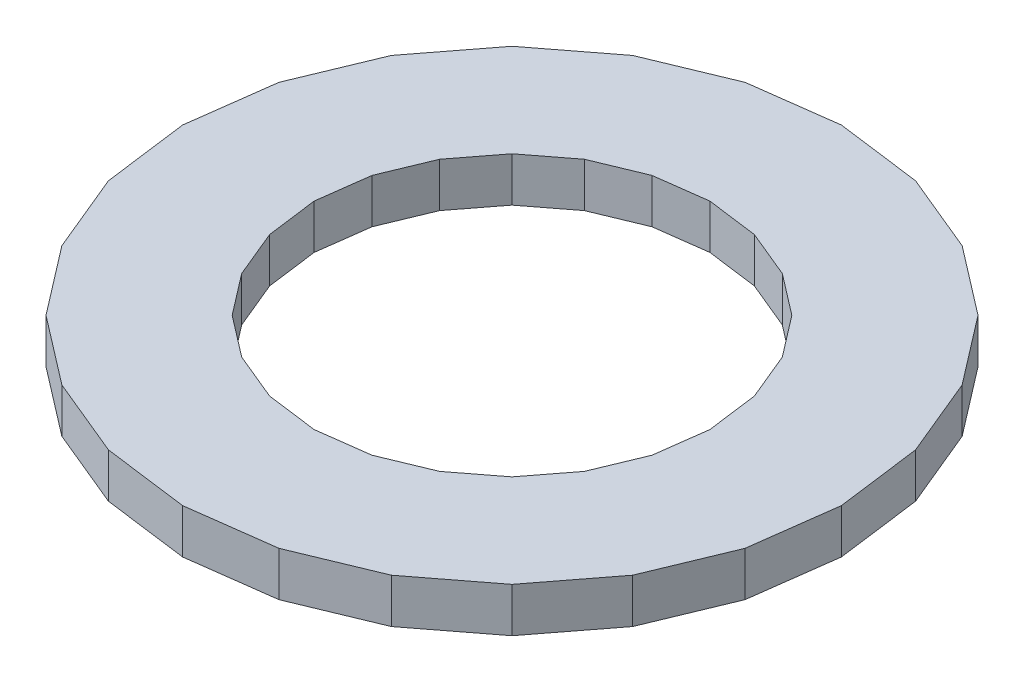
SolidWorks part; units mm, degrees
ref_plane "Front Plane" through (0, 0, 0) normal (0, 0, 1) x (1, 0, 0)
ref_plane "Top Plane" through (0, 0, 0) normal (0, 1, 0) x (1, 0, 0)
ref_plane "Right Plane" through (0, 0, 0) normal (1, 0, 0) x (0, 0, -1)
sketch "Sketch2" plane through (0, 0, 0) normal (0, 1, 0) x (1, 0, 0)
  line L0 (0, 0) -> (-84.7206, 0) construction
  line L1 (-141.0828, 0) -> (-136.2755, -36.5149)
  line L2 (-136.2755, -36.5149) -> (-122.1813, -70.5414)
  line L3 (-122.1813, -70.5414) -> (-99.7606, -99.7606)
  line L4 (-99.7606, -99.7606) -> (-70.5414, -122.1813)
  line L5 (-70.5414, -122.1813) -> (-36.5149, -136.2755)
  line L6 (-36.5149, -136.2755) -> (0, -141.0828)
  line L7 (0, -141.0828) -> (36.5149, -136.2755)
  line L8 (36.5149, -136.2755) -> (70.5414, -122.1813)
  line L9 (70.5414, -122.1813) -> (99.7606, -99.7606)
  line L10 (99.7606, -99.7606) -> (122.1813, -70.5414)
  line L11 (122.1813, -70.5414) -> (136.2755, -36.5149)
  line L12 (136.2755, -36.5149) -> (141.0828, 0)
  line L13 (141.0828, 0) -> (136.2755, 36.5149)
  line L14 (136.2755, 36.5149) -> (122.1813, 70.5414)
  line L15 (122.1813, 70.5414) -> (99.7606, 99.7606)
  line L16 (99.7606, 99.7606) -> (70.5414, 122.1813)
  line L17 (70.5414, 122.1813) -> (36.5149, 136.2755)
  line L18 (36.5149, 136.2755) -> (0, 141.0828)
  line L19 (0, 141.0828) -> (-36.5149, 136.2755)
  line L20 (-36.5149, 136.2755) -> (-70.5414, 122.1813)
  line L21 (-70.5414, 122.1813) -> (-99.7606, 99.7606)
  line L22 (-99.7606, 99.7606) -> (-122.1813, 70.5414)
  line L23 (-122.1813, 70.5414) -> (-136.2755, 36.5149)
  line L24 (-136.2755, 36.5149) -> (-141.0828, 0)
  line L25 (-84.7206, 0) -> (-81.8338, -21.9273)
  line L26 (-81.8338, -21.9273) -> (-73.3702, -42.3603)
  line L27 (-73.3702, -42.3603) -> (-59.9065, -59.9065)
  line L28 (-59.9065, -59.9065) -> (-42.3603, -73.3702)
  line L29 (-42.3603, -73.3702) -> (-21.9273, -81.8338)
  line L30 (-21.9273, -81.8338) -> (0, -84.7206)
  line L31 (0, -84.7206) -> (21.9273, -81.8338)
  line L32 (21.9273, -81.8338) -> (42.3603, -73.3702)
  line L33 (42.3603, -73.3702) -> (59.9065, -59.9065)
  line L34 (59.9065, -59.9065) -> (73.3702, -42.3603)
  line L35 (73.3702, -42.3603) -> (81.8338, -21.9273)
  line L36 (81.8338, -21.9273) -> (84.7206, 0)
  line L37 (84.7206, 0) -> (81.8338, 21.9273)
  line L38 (81.8338, 21.9273) -> (73.3702, 42.3603)
  line L39 (73.3702, 42.3603) -> (59.9065, 59.9065)
  line L40 (59.9065, 59.9065) -> (42.3603, 73.3702)
  line L41 (42.3603, 73.3702) -> (21.9273, 81.8338)
  line L42 (21.9273, 81.8338) -> (0, 84.7206)
  line L43 (0, 84.7206) -> (-21.9273, 81.8338)
  line L44 (-21.9273, 81.8338) -> (-42.3603, 73.3702)
  line L45 (-42.3603, 73.3702) -> (-59.9065, 59.9065)
  line L46 (-59.9065, 59.9065) -> (-73.3702, 42.3603)
  line L47 (-73.3702, 42.3603) -> (-81.8338, 21.9273)
  line L48 (-81.8338, 21.9273) -> (-84.7206, 0)
  line L49 (-141.0828, 0) -> (-84.7206, 0) construction
  circle A0 centre (0, 0) radius 139.8758 construction
  circle A1 centre (0, 0) radius 83.9958 construction
  dimension "D1" = 36.83
  dimension "D2" = 55.88
extrude "Boss-Extrude2" add sketch "Sketch2" along normal blind 19.05
